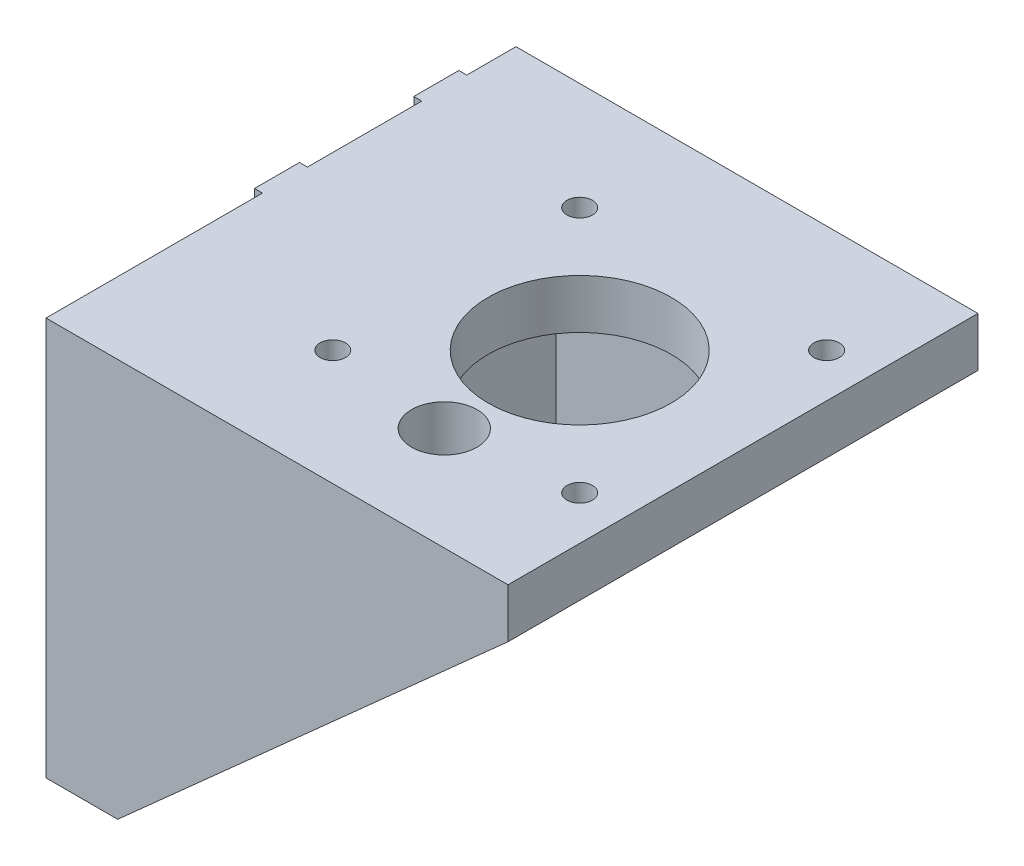
SolidWorks part; units mm, degrees
ref_plane "Plano frontal" through (0, 0, 0) normal (0, 0, 1) x (1, 0, 0)
ref_plane "Plano superior" through (0, 0, 0) normal (0, 1, 0) x (1, 0, 0)
ref_plane "Plano direito" through (0, 0, 0) normal (1, 0, 0) x (0, 0, -1)
sketch "Esboço1" plane through (0, 0, 0) normal (0, 0, 1) x (1, 0, 0)
  line L0 (9, 0) -> (58, 43.8)
  line L1 (0, 50) -> (58, 50)
  line L2 (0, 50) -> (0, 0)
  line L3 (0, 0) -> (9, 0)
  line L4 (58, 50) -> (58, 43.8)
  point P0 (0, 0)
  dimension "D1" = 58
  dimension "D2" = 9
  dimension "D3" = 6.2
  dimension "D4" = 50
extrude "Ressalto-extrusão1" add sketch "Esboço1" along normal blind 59
sketch "Esboço2" plane through (58, 0, 0) normal (1, 0, 0) x (0, 0, -1)
  line L0 (-54, 43.8) -> (-4, 43.8)
  line L1 (-59, 43.8) -> (0, 43.8) construction
  line L2 (-4, 43.8) -> (-4, 0)
  line L3 (-59, 0) -> (0, 0) construction
  line L4 (-4, 0) -> (-54, 0)
  line L5 (-54, 0) -> (-54, 43.8)
  line L6 (-59, 0) -> (-59, 43.8) construction
  line L7 (0, 0) -> (0, 43.8) construction
  dimension "D1" = 5
  dimension "D2" = 4
extrude "Corte-extrusão1" cut sketch "Esboço2" against normal offset from surface (49 mm away) 9 up to face at (0, 25, 29.5)
sketch "Esboço3" plane through (9, 0, 0) normal (1, 0, 0) x (0, 0, -1)
  line L0 (-29, 31.9) -> (-29, 11.9) construction
  line L3 (-59, 0) -> (-59, 43.8) construction
  line L4 (-59, 21.9) -> (0, 21.9) construction
  line L5 (0, 0) -> (0, 43.8) construction
  line L6 (-29, 0) -> (-29, 7.3672) construction
  line L7 (-4, 0) -> (-54, 0) construction
  line L8 (-9, 31.9) -> (-9, 11.9) construction
  circle A0 centre (-29, 11.9) radius 1.75
  circle A1 centre (-29, 31.9) radius 1.75
  circle A2 centre (-9, 31.9) radius 1.75
  circle A3 centre (-9, 11.9) radius 1.75
  point P0 (-29, 21.9)
  point P22 (-9, 21.9)
  dimension "D1" = 3.5
  dimension "D2" = 20
  dimension "D3" = 20
extrude "Corte-extrusão2" cut sketch "Esboço3" against normal through all
sketch "Esboço4" plane through (0, 0, 0) normal (-1, 0, 0) x (0, 0, 1)
  line L0 (6.175, 50) -> (6.175, 0)
  line L1 (59, 50) -> (0, 50) construction
  line L2 (59, 0) -> (0, 0) construction
  line L3 (6.175, 0) -> (11.825, 0)
  line L4 (11.825, 0) -> (11.825, 50)
  line L5 (11.825, 50) -> (6.175, 50)
  line L6 (9, 50) -> (9, 0) construction
  line L7 (26.175, 50) -> (26.175, 0)
  line L8 (26.175, 0) -> (31.825, 0)
  line L9 (31.825, 0) -> (31.825, 50)
  line L10 (31.825, 50) -> (26.175, 50)
  line L11 (29, 50) -> (29, 0) construction
  circle A0 centre (9, 31.9) radius 1.75 construction
  circle A1 centre (9, 31.9) radius 1.75 construction
  circle A2 centre (29, 31.9) radius 1.75 construction
  circle A3 centre (29, 31.9) radius 1.75 construction
  circle M13 centre (9, 11.9) radius 1.75
  circle M14 centre (9, 31.9) radius 1.75
  circle M15 centre (29, 31.9) radius 1.75
  circle M16 centre (29, 11.9) radius 1.75
  line M18 (0, 0) -> (59, 0)
  line M20 (59, 50) -> (0, 50)
  dimension "D1" = 5.65
  dimension "D2" = 5.65
extrude "Ressalto-extrusão2" add sketch "Esboço4" along normal blind 1 contours L4 L0 M18 M20 M13 M14 | L9 L7 M18 M20 M16 M15
sketch "Esboço5" plane through (9, 0, 0) normal (1, 0, 0) x (0, 0, -1)
  circle A0 centre (-29, 31.9) radius 4.35
  circle A1 centre (-9, 31.9) radius 4.35
  circle A2 centre (-29, 11.9) radius 4.35
  circle A3 centre (-9, 11.9) radius 4.35
  dimension "D1" = 8.7
extrude "Corte-extrusão3" cut sketch "Esboço5" against normal blind 4
sketch "Esboço6" plane through (0, 50, 0) normal (0, 1, 0) x (1, 0, 0)
  line L0 (58, 0) -> (0, 0) construction
  line L1 (58, -59) -> (58, 0) construction
  line L3 (52.5, -44.5) -> (21.5, -44.5) construction
  line L4 (52.5, -44.5) -> (52.5, -13.5) construction
  line L5 (52.5, -13.5) -> (21.5, -13.5) construction
  line L6 (21.5, -44.5) -> (21.5, -13.5) construction
  line L7 (52.5, -44.5) -> (21.5, -13.5) construction
  line L8 (52.5, -13.5) -> (21.5, -44.5) construction
  line L9 (37, -29) -> (37, -46) construction
  circle A0 centre (37, -29) radius 11.5
  circle A1 centre (21.5, -13.5) radius 1.6
  circle A2 centre (52.5, -13.5) radius 1.6
  circle A3 centre (52.5, -44.5) radius 1.6
  circle A4 centre (21.5, -44.5) radius 1.6
  circle A5 centre (37, -46) radius 4.1
  dimension "D3" = 23
  dimension "D6" = 3.2
  dimension "D7" = 8.2
  dimension "D1" = 29
  dimension "D2" = 21
  dimension "D4" = 31
  dimension "D5" = 31
  dimension "D8" = 17
extrude "Corte-extrusão4" cut sketch "Esboço6" against normal up to surface (6.2 mm away) up to face at (33.5, 43.8, 29)
equation "\"`9\"=10.8324"
